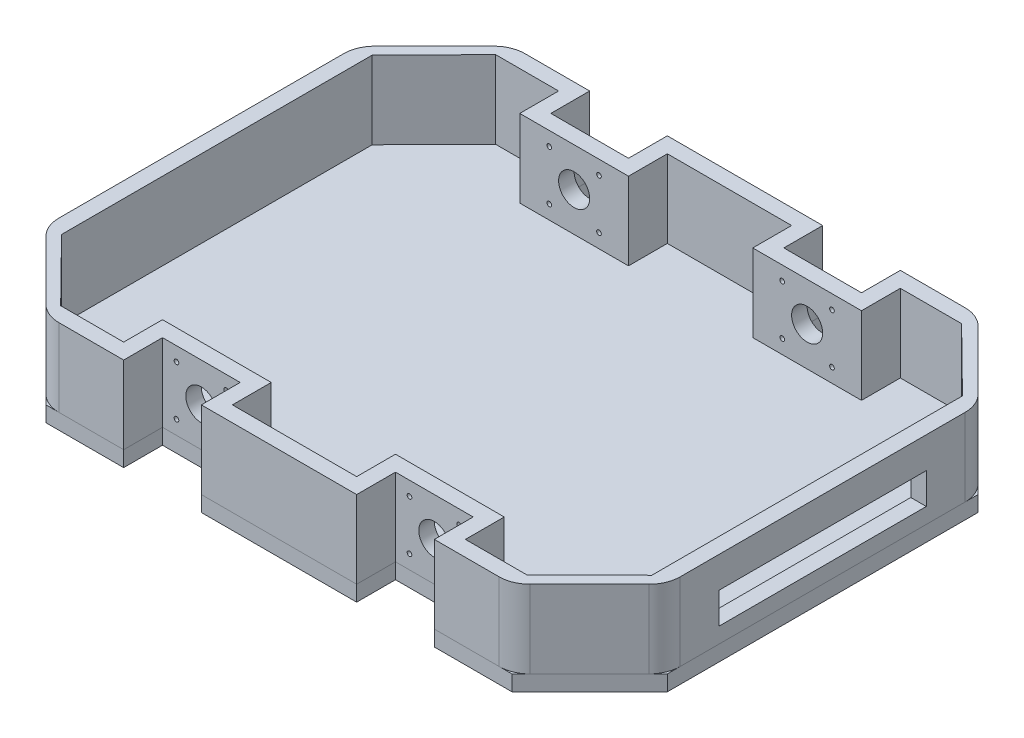
SolidWorks part; units mm, degrees
ref_plane "Front Plane" through (0, 0, 0) normal (0, 0, 1) x (1, 0, 0)
ref_plane "Top Plane" through (0, 0, 0) normal (0, 1, 0) x (1, 0, 0)
ref_plane "Right Plane" through (0, 0, 0) normal (1, 0, 0) x (0, 0, -1)
sketch "Sketch1" plane through (0, 0, 0) normal (0, 1, 0) x (1, 0, 0)
  line L116 (-237.6523, 68.3076) -> (-237.6523, 68.4174)
  line L118 (-272.6311, 90.2769) -> (-222.6311, 90.2769)
  line L119 (-222.6311, 90.2769) -> (-222.6311, 65.2769)
  line L120 (-222.6311, 65.2769) -> (-172.6311, 65.2769)
  line L121 (-172.6311, 65.2769) -> (-172.6311, 90.2769)
  line L122 (-172.6311, 90.2769) -> (-72.6311, 90.2769)
  line L123 (-72.6311, 90.2769) -> (-72.6311, 65.2769)
  line L124 (-72.6311, 65.2769) -> (-22.6311, 65.2769)
  line L125 (-22.6311, 65.2769) -> (-22.6311, 90.2769)
  line L126 (-22.6311, 90.2769) -> (27.3689, 90.2769)
  line L127 (27.3689, 90.2769) -> (77.3689, 40.2769)
  line L133 (-272.6311, 90.2769) -> (-322.6311, 40.2769)
  line L134 (-322.6311, 40.2769) -> (-322.6311, -159.7231)
  line L136 (77.3689, -159.7231) -> (77.3689, 40.2769)
  line L138 (-312.6311, -159.7231) -> (-312.6311, 40.2769)
  line L139 (-312.6311, 40.2769) -> (-273.1946, 80.2769)
  line L140 (-273.1946, 80.2769) -> (-232.6311, 80.2769)
  line L141 (-232.6311, 80.2769) -> (-232.6311, 55.2769)
  line L142 (-232.6311, 55.2769) -> (-162.6311, 55.2769)
  line L143 (-162.6311, 55.2769) -> (-162.6311, 80.2769)
  line L144 (-162.6311, 80.2769) -> (-82.6311, 80.2769)
  line L145 (-82.6311, 80.2769) -> (-82.6311, 55.2769)
  line L146 (-82.6311, 55.2769) -> (-12.6311, 55.2769)
  line L147 (-12.6311, 55.2769) -> (-12.6311, 80.2769)
  line L148 (-12.6311, 80.2769) -> (26.7974, 80.2769)
  line L149 (26.7974, 80.2769) -> (67.3689, 40.2769)
  line L150 (67.3689, 40.2769) -> (67.3689, -159.7231)
  line L152 (26.7974, -199.7231) -> (67.3689, -159.7231)
  line L153 (-12.6311, -199.7231) -> (26.7974, -199.7231)
  line L154 (-12.6311, -174.7231) -> (-12.6311, -199.7231)
  line L155 (-82.6311, -174.7231) -> (-12.6311, -174.7231)
  line L156 (-82.6311, -199.7231) -> (-82.6311, -174.7231)
  line L157 (-162.6311, -199.7231) -> (-82.6311, -199.7231)
  line L158 (-162.6311, -174.7231) -> (-162.6311, -199.7231)
  line L159 (-232.6311, -174.7231) -> (-162.6311, -174.7231)
  line L160 (-232.6311, -199.7231) -> (-232.6311, -174.7231)
  line L161 (-273.1946, -199.7231) -> (-232.6311, -199.7231)
  line L162 (-312.6311, -159.7231) -> (-273.1946, -199.7231)
  line L163 (-272.6311, -209.7231) -> (-322.6311, -159.7231)
  line L164 (27.3689, -209.7231) -> (77.3689, -159.7231)
  line L165 (-22.6311, -209.7231) -> (27.3689, -209.7231)
  line L166 (-22.6311, -184.7231) -> (-22.6311, -209.7231)
  line L167 (-72.6311, -184.7231) -> (-22.6311, -184.7231)
  line L168 (-72.6311, -209.7231) -> (-72.6311, -184.7231)
  line L169 (-172.6311, -209.7231) -> (-72.6311, -209.7231)
  line L170 (-172.6311, -184.7231) -> (-172.6311, -209.7231)
  line L171 (-222.6311, -184.7231) -> (-172.6311, -184.7231)
  line L172 (-222.6311, -209.7231) -> (-222.6311, -184.7231)
  line L173 (-272.6311, -209.7231) -> (-222.6311, -209.7231)
  point P10 (-22.6311, 77.7769)
  dimension "D1" = 50
  dimension "D2" = 50
  dimension "D3" = 50
  dimension "D4" = 100
  dimension "D5" = 50
  dimension "D6" = 50
  dimension "D7" = 50
  dimension "D8" = 50
  dimension "D9" = 50
  dimension "D10" = 25
  dimension "D11" = 25
  dimension "D12" = 25
  dimension "D13" = 25
  dimension "D14" = 400
  dimension "D15" = 300
  dimension "D16" = 10
  dimension "D17" = 10
  dimension "D18" = 10
  dimension "D19" = 10
  dimension "D20" = 10
  dimension "D21" = 10
  dimension "D22" = 10
  dimension "D23" = 10
  dimension "D24" = 10
  dimension "D25" = 10
  dimension "D26" = 10
extrude "Boss-Extrude2" add sketch "Sketch1" along normal blind 50 contours L163 L173 L172 L171 L170 L169 L168 L167 L166 L165 L164 L136 L127 L126 L125 L124 L123 L122 L121 L120 L119 L118 L133 L134 L162 L138 L139 L140 L141 L142 L143 L144 L145 L146 L147 L148 L149 L150 L152 L153 L154 L155 L156 L157 L158 L159 L160 L161
sketch "Sketch5" plane through (0, 0, 0) normal (0, 1, 0) x (1, 0, 0)
  line L0 (-322.6311, 40.2769) -> (-322.6311, -159.7231)
  line L1 (-322.6311, -159.7231) -> (-272.6311, -209.7231)
  line L2 (-272.6311, -209.7231) -> (-222.6311, -209.7231)
  line L3 (-222.6311, -209.7231) -> (-222.6311, -184.7231)
  line L4 (-222.6311, -184.7231) -> (-172.6311, -184.7231)
  line L5 (-172.6311, -184.7231) -> (-172.6311, -209.7231)
  line L6 (-172.6311, -209.7231) -> (-72.6311, -209.7231)
  line L7 (-72.6311, -209.7231) -> (-72.6311, -184.7231)
  line L8 (-72.6311, -184.7231) -> (-22.6311, -184.7231)
  line L9 (-22.6311, -184.7231) -> (-22.6311, -209.7231)
  line L10 (-22.6311, -209.7231) -> (27.3689, -209.7231)
  line L11 (27.3689, -209.7231) -> (77.3689, -159.7231)
  line L12 (77.3689, -159.7231) -> (77.3689, 40.2769)
  line L13 (77.3689, 40.2769) -> (27.3689, 90.2769)
  line L14 (27.3689, 90.2769) -> (-22.6311, 90.2769)
  line L15 (-22.6311, 90.2769) -> (-22.6311, 65.2769)
  line L16 (-22.6311, 65.2769) -> (-72.6311, 65.2769)
  line L17 (-72.6311, 65.2769) -> (-72.6311, 90.2769)
  line L18 (-72.6311, 90.2769) -> (-172.6311, 90.2769)
  line L19 (-172.6311, 90.2769) -> (-172.6311, 65.2769)
  line L20 (-172.6311, 65.2769) -> (-222.6311, 65.2769)
  line L21 (-222.6311, 65.2769) -> (-222.6311, 90.2769)
  line L22 (-222.6311, 90.2769) -> (-272.6311, 90.2769)
  line L23 (-272.6311, 90.2769) -> (-322.6311, 40.2769)
extrude "Boss-Extrude4" add sketch "Sketch5" against normal blind 10
sketch "Sketch6" plane through (0, 0, 184.7231) normal (0, 0, 1) x (1, 0, 0)
  line L0 (-72.6311, -10) -> (-22.6311, -10) construction
  line L7 (-63.6311, 9) -> (-31.6311, 9) construction
  line L8 (-63.6311, 9) -> (-63.6311, 41) construction
  line L9 (-63.6311, 41) -> (-31.6311, 41) construction
  line L10 (-31.6311, 9) -> (-31.6311, 41) construction
  line L11 (-63.6311, 9) -> (-31.6311, 41) construction
  line L12 (-63.6311, 41) -> (-31.6311, 9) construction
  circle A0 centre (-47.6311, 25) radius 10
  circle A1 centre (-31.6311, 41) radius 1.5
  circle A2 centre (-63.6311, 41) radius 1.5
  circle A3 centre (-63.6311, 9) radius 1.5
  circle A4 centre (-31.6311, 9) radius 1.5
  dimension "D1" = 20
  dimension "D6" = 3
  dimension "D7" = 3
  dimension "D4" = 3
  dimension "D5" = 3
  dimension "D2" = 16
  dimension "D3" = 16
  dimension "D8" = 35
extrude "Cut-Extrude3" cut sketch "Sketch6" against normal through all
sketch "Sketch8" plane through (0, 0, 184.7231) normal (0, 0, 1) x (1, 0, 0)
  line L0 (-197.6311, 46.0987) -> (-197.6311, 3.9013) construction
  line L1 (-172.6311, 50) -> (-172.6311, 0) construction
  line L2 (-213.6311, 9) -> (-181.6311, 9) construction
  line L3 (-213.6311, 9) -> (-213.6311, 41) construction
  line L4 (-213.6311, 41) -> (-181.6311, 41) construction
  line L5 (-181.6311, 9) -> (-181.6311, 41) construction
  line L6 (-213.6311, 9) -> (-181.6311, 41) construction
  line L7 (-213.6311, 41) -> (-181.6311, 9) construction
  line L8 (-222.6311, -10) -> (-172.6311, -10) construction
  circle A0 centre (-197.6311, 25) radius 10
  circle A1 centre (-181.6311, 41) radius 1.5
  circle A2 centre (-213.6311, 41) radius 1.5
  circle A3 centre (-213.6311, 9) radius 1.5
  circle A4 centre (-181.6311, 9) radius 1.5
  dimension "D1" = 20
  dimension "D4" = 3
  dimension "D5" = 3
  dimension "D6" = 3
  dimension "D7" = 3
  dimension "D2" = 16
  dimension "D3" = 16
  dimension "D8" = 35
  dimension "D9" = 25
extrude "Cut-Extrude4" cut sketch "Sketch8" against normal through all
fillet "Fillet2" radius 20 8 edges at (27.3689, 25, 209.7231) (77.3689, 25, 159.7231) (77.3689, 25, -40.2769) (27.3689, 25, -90.2769) (-272.6311, 25, -90.2769) (-272.6311, 25, 209.7231) (-322.6311, 25, 159.7231) (-322.6311, 25, -40.2769)
sketch "Sketch9" plane through (77.3689, 0, 0) normal (1, 0, 0) x (0, 0, -1)
  line L0 (-151.4389, 50) -> (-151.4389, 0) construction
  line L1 (-126.4389, 30) -> (6.9926, 30)
  line L2 (-126.4389, 30) -> (-126.4389, 10)
  line L3 (-126.4389, 10) -> (6.9926, 10)
  line L4 (6.9926, 30) -> (6.9926, 10)
  line L5 (-126.4389, 30) -> (6.9926, 10) construction
  line L6 (-126.4389, 10) -> (6.9926, 30) construction
  line L7 (31.9926, 0) -> (31.9926, 50) construction
  line L8 (-151.4389, 50) -> (31.9926, 50) construction
  line L9 (-159.7231, -10) -> (40.2769, -10) construction
  point P0 (-59.7231, 20)
  dimension "D1" = 25
  dimension "D2" = 25
  dimension "D3" = 20
  dimension "D4" = 20
extrude "Cut-Extrude5" cut sketch "Sketch9" against normal up to next (10 mm away)
